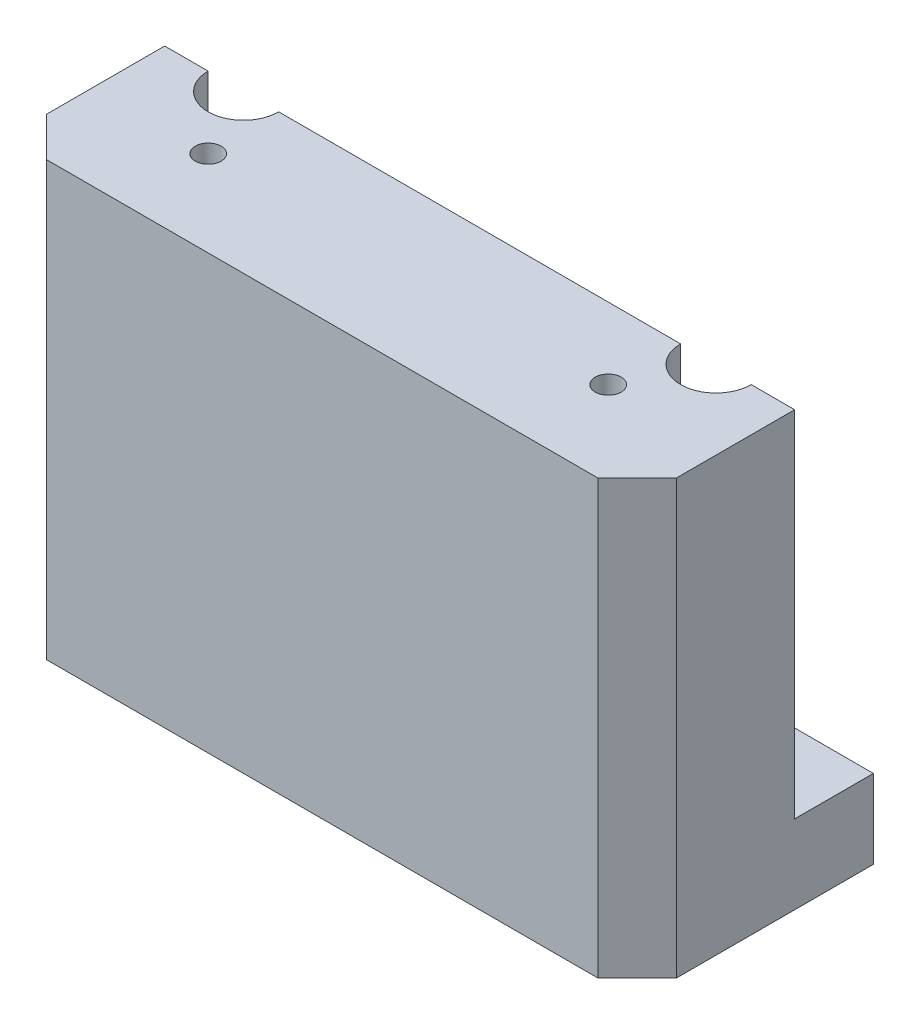
SolidWorks part; units mm, degrees
ref_plane "Front Plane" through (0, 0, 0) normal (0, 0, 1) x (1, 0, 0)
ref_plane "Top Plane" through (0, 0, 0) normal (0, 1, 0) x (1, 0, 0)
ref_plane "Right Plane" through (0, 0, 0) normal (1, 0, 0) x (0, 0, -1)
sketch "Sketch1" plane through (0, 0, 0) normal (0, 1, 0) x (1, 0, 0)
  line L1 (-40, -15) -> (40, -15)
  line L2 (-40, -15) -> (-40, 15)
  line L3 (-40, 15) -> (40, 15)
  line L4 (40, -15) -> (40, 15)
  line L5 (-40, -15) -> (40, 15) construction
  line L6 (-40, 15) -> (40, -15) construction
  point P0 (0, 0)
  dimension "D1" = 80
  dimension "D2" = 30
extrude "Boss-Extrude1" add sketch "Sketch1" along normal blind 55
hole_wizard "CSK for M4 SFHCS1" positions "Sketch3" profile "Sketch5" countersink size "M4" standard "ANSI Metric" end condition through all
sketch "Sketch3" plane through (0, 55, 0) normal (0, 1, 0) x (1, 0, 0)
  line L0 (-30, 5) -> (30, 5)
  line L1 (40, 15) -> (-40, 15) construction
  point P0 (-30, 5)
  point P1 (30, 5)
  point P14 (0, 5)
  dimension "D1" = 60
  dimension "D2" = 10
sketch "Sketch5" plane through (-30, 55, -5) normal (1, 0, 0) x (0, 0, 1)
  line L0 (0, 0) -> (0, 55)
  line L1 (0, 55) -> (2.25, 55)
  line L2 (2.25, 55) -> (2.25, 47.23)
  line L3 (2.25, 47.23) -> (4.48, 45)
  line L4 (4.48, 45) -> (4.48, 0)
  line L6 (4.48, 0) -> (0, 0)
  line L7 (-2.25, 47.23) -> (-4.48, 45) construction
  line L11 (0, -6.35) -> (0, 107.95) construction
  dimension "Thru Hole Dia." = 4.5
  dimension "Thru Hole Depth" = 55
  dimension "C'Sink Dia." = 8.96
  dimension "C'Sink Angle" = 90
  dimension "Head Clearance" = 45
hole_wizard "M4x0.7 Tapped Hole1" positions "Sketch6" profile "Sketch8" tap size "M4x0.7" standard "ANSI Metric"
sketch "Sketch6" plane through (0, 55, 0) normal (0, 1, 0) x (1, 0, 0)
  line L0 (-25.4, -4.078) -> (25.4, -4.078)
  line L2 (-40, -15) -> (40, -15) construction
  point P1 (-25.4, -4.078)
  point P2 (25.4, -4.078)
  point P7 (0, -4.078)
  dimension "D1" = 50.8
  dimension "D2" = 10.922
sketch "Sketch8" plane through (-25.4, 55, 4.078) normal (1, 0, 0) x (0, 0, 1)
  line L0 (0, 0) -> (0, 20.9914)
  line L1 (0, 20.9914) -> (1.65, 20)
  line L2 (1.65, 20) -> (1.65, 0)
  line L5 (1.65, 0) -> (0, 0)
  line L10 (0, 20.9914) -> (-1.65, 20) construction
  line L11 (0, -6.35) -> (0, 107.95) construction
  dimension "Tap Drill Dia." = 3.3
  dimension "Tap Drill Depth" = 20
  dimension "Drill Angle" = 118
cosmetic thread "Hole Thread1" parameters "D1"=8, "D2"=4
cosmetic thread "Hole Thread2" parameters "D1"=8, "D2"=4
chamfer "Chamfer1" distance 5 angle 45 2 edges at (-40, 27.5, 15) (40, 27.5, 15)
sketch "Sketch9" plane through (0, 0, -15) normal (0, 0, -1) x (-1, 0, 0)
  line L1 (-40, 55) -> (-40, 0) construction
  line L2 (40, 55) -> (40, 0) construction
  line L4 (-40, 10) -> (40, 10)
  line L5 (-40, 10) -> (-40, 55)
  line L6 (-40, 55) -> (40, 55)
  line L7 (40, 10) -> (40, 55)
  dimension "D1" = 10
extrude "Cut-Extrude1" cut sketch "Sketch9" against normal blind 10 contours L5 L4 L7 L6
